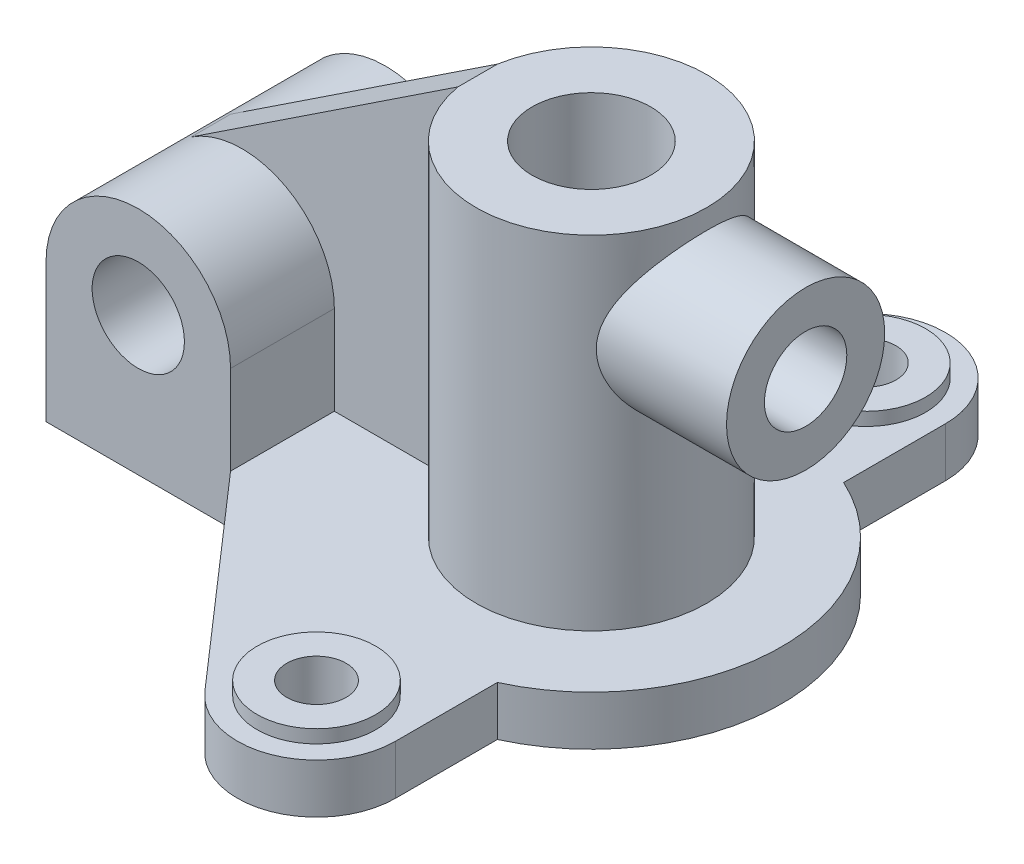
SolidWorks part; units mm, degrees
ref_plane "Front Plane" through (0, 0, 0) normal (0, 0, 1) x (1, 0, 0)
ref_plane "Top Plane" through (0, 0, 0) normal (0, 1, 0) x (1, 0, 0)
ref_plane "Right Plane" through (0, 0, 0) normal (1, 0, 0) x (0, 0, -1)
sketch "Sketch1" plane through (0, 0, 0) normal (0, 1, 0) x (1, 0, 0)
  line L2 (609.6, 2119.0193) -> (609.6, 1334.3598)
  line L3 (-1828.8, -952.5) -> (-1828.8, 952.5)
  line L4 (-1828.8, 952.5) -> (-459.0495, 2520.1249)
  line L5 (609.6, -2119.0193) -> (609.6, -1334.3598)
  line L6 (-1828.8, -952.5) -> (-459.0495, -2520.1249)
  arc A0 (609.6, -1334.3598) -> (609.6, 1334.3598) centre (0, 0) ccw
  arc A1 (609.6, 2119.0193) -> (-459.0495, 2520.1249) centre (0, 2119.0193) ccw
  arc A3 (609.6, -2119.0193) -> (-459.0495, -2520.1249) centre (0, -2119.0193) cw
  dimension "D1" = 1219.2
extrude "Boss-Extrude1" add sketch "Sketch1" along normal blind 381
sketch "Sketch2" plane through (0, 0, 0) normal (0, 1, 0) x (1, 0, 0)
  circle A0 centre (0, 0) radius 889
  dimension "D1" = 1778
extrude "Boss-Extrude2" add sketch "Sketch2" along normal blind 3022.6
sketch "Sketch4" plane through (0, 0, 0) normal (0, 1, 0) x (1, 0, 0)
  circle A3 centre (0, -2119.0193) radius 228.6
  circle A4 centre (0, -2119.0193) radius 457.2
  circle A5 centre (0, 2119.0193) radius 457.2
  circle A6 centre (0, 2119.0193) radius 228.6
extrude "Boss-Extrude3" add sketch "Sketch4" along normal blind 482.6
sketch "Sketch5" plane through (0, 381, 0) normal (0, 1, 0) x (1, 0, 0)
  circle A0 centre (0, 2119.0193) radius 228.6
  circle A1 centre (0, -2119.0193) radius 228.6
extrude "Cut-Extrude2" cut sketch "Sketch5" against normal up to next
sketch "Sketch6" plane through (0, 0, 0) normal (1, 0, 0) x (0, 0, -1)
  circle A0 centre (0, 2260.6) radius 609.6
extrude "Boss-Extrude4" add sketch "Sketch6" along normal blind 1651
sketch "Sketch7" plane through (1651, 0, 0) normal (1, 0, 0) x (0, 0, -1)
  circle A0 centre (0, 2260.6) radius 317.5
extrude "Cut-Extrude3" cut sketch "Sketch7" against normal blind 1651
sketch "Sketch8" plane through (0, 3022.6, 0) normal (0, 1, 0) x (1, 0, 0)
  circle A0 centre (0, 0) radius 457.2
extrude "Cut-Extrude4" cut sketch "Sketch8" against normal blind 3022.6
sketch "Sketch10" plane through (0, 0, 0) normal (0, 1, 0) x (1, 0, 0)
  line L0 (-1828.8, -952.5) -> (-3251.2, -952.5)
  line L1 (-3251.2, -952.5) -> (-3251.2, 952.5)
  line L2 (-3251.2, 952.5) -> (-1828.8, 952.5)
  line L3 (-1828.8, 952.5) -> (-1828.8, -952.5)
extrude "Boss-Extrude5" add sketch "Sketch10" along normal blind 1778
sketch "Sketch11" plane through (0, 0, 952.5) normal (0, 0, 1) x (1, 0, 0)
  line L4 (-3251.2, 1066.8) -> (-3251.2, 1778)
  line L5 (-3251.2, 1778) -> (-1828.8, 1778)
  line L6 (-1828.8, 1778) -> (-1828.8, 1066.8)
  arc A0 (-1828.8, 1066.8) -> (-3251.2, 1066.8) centre (-2540, 1066.8) ccw
  line M10 (-1828.8, 381) -> (-1828.8, 1778)
  line M11 (-1828.8, 1778) -> (-3251.2, 1778)
  line M12 (-3251.2, 1778) -> (-3251.2, 0)
extrude "Cut-Extrude5" cut sketch "Sketch11" against normal up to next contours A0 L5 M12 | A0 M10 M11
sketch "Sketch12" plane through (0, 0, 952.5) normal (0, 0, 1) x (1, 0, 0)
  circle A0 centre (-2540, 1066.8) radius 355.6
extrude "Cut-Extrude6" cut sketch "Sketch12" against normal up to next
sketch "Sketch15" plane through (0, 3022.6, 0) normal (0, 1, 0) x (1, 0, 0)
  line L2 (-875.8397, 152.4) -> (-3251.2, 152.4)
  line L3 (-875.8397, -152.4) -> (-3251.2, -152.4)
  line L4 (-3251.2, 152.4) -> (-3251.2, -152.4)
  circle A0 centre (0, 0) radius 889 construction
  circle A1 centre (0, 0) radius 889 construction
  arc A2 (-875.8397, 152.4) -> (-875.8397, -152.4) centre (0, 0) ccw
extrude "Boss-Extrude10" add sketch "Sketch15" against normal blind 3022.6
sketch "Sketch16" plane through (0, 0, 152.4) normal (0, 0, 1) x (1, 0, 0)
  line L0 (-875.8397, 3022.6) -> (-2932.8265, 1659.6683)
  line L1 (-875.8397, 3022.6) -> (-3251.2, 3022.6)
  line L2 (-3251.2, 3022.6) -> (-3251.2, 1066.8)
  line L3 (-3251.2, 1066.8) -> (-3251.2, 3022.6) construction
  arc A0 (-1828.8, 1066.8) -> (-3251.2, 1066.8) centre (-2540, 1066.8) ccw construction
  arc A1 (-1828.8, 1066.8) -> (-3251.2, 1066.8) centre (-2540, 1066.8) ccw construction
  arc A2 (-2932.8265, 1659.6683) -> (-3251.2, 1066.8) centre (-2540, 1066.8) ccw
extrude "Cut-Extrude7" cut sketch "Sketch16" against normal up to next
